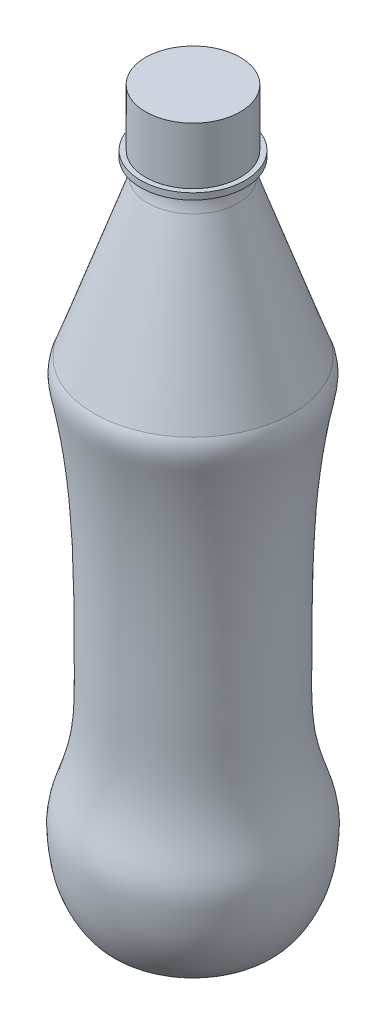
SolidWorks part; units mm, degrees
ref_plane "Front Plane" through (0, 0, 0) normal (0, 0, 1) x (1, 0, 0)
ref_plane "Top Plane" through (0, 0, 0) normal (0, 1, 0) x (1, 0, 0)
ref_plane "Right Plane" through (0, 0, 0) normal (1, 0, 0) x (0, 0, -1)
sketch "Sketch2" plane through (0, 0, 0) normal (0, 0, 1) x (1, 0, 0)
  line L0 (0, 168.9032) -> (0, -61.0968) construction
  line L1 (0, 168.9032) -> (15, 168.9032)
  line L2 (15, 168.9032) -> (15, 150.9032)
  line L3 (15, 150.9032) -> (16.6, 150.9032)
  line L4 (16.6, 150.9032) -> (16.6, 148.9032)
  line L5 (0, 148.9032) -> (13.5, 148.9032) construction
  line L6 (16.6, 148.9032) -> (13.5, 148.9032)
  line L7 (0, 88.9032) -> (32.5, 88.9032) construction
  line L8 (0, -36.0968) -> (32.75, -36.0968) construction
  line L9 (0, -31.0968) -> (32.7, -31.0968) construction
  line L10 (0, -21.0968) -> (30, -21.0968) construction
  line L11 (0, -11.0968) -> (27.6, -11.0968) construction
  line L12 (14.3221, 143.4974) -> (31.45, 94.2716)
  line L13 (0, 8.9032) -> (26.65, 8.9032) construction
  line L14 (0, 168.9032) -> (0, -55.3348)
  line L16 (0, 83.9032) -> (31.7, 83.9032) construction
  spline S0 degree 3 poles (13.5, 148.9032) (13.4345, 147.0626) (13.7086, 145.2606) (14.3221, 143.4974) knots 0 0 0 0 1 1 1 1
  spline S1 degree 3 poles (31.45, 94.2716) (33.2291, 90.845) (26.5516, 62.4338) (26.8239, 27.6424) (26.5349, -7.9803) (29.7799, -21.1671) (32.9574, -29.251) (32.6954, -40.3545) (31.0423, -50.9398) (22.168, -63.1456) (13.0307, -58.7237) (6.8276, -55.3682) (1.9563, -55.269) (0, -55.3348) knots 0 0 0 0 0.057803 0.472965 0.582838 0.63927 0.696109 0.723548 0.819703 0.882565 0.920544 0.968756 1 1 1 1
  dimension "D1" = 2
  dimension "D2" = 15
  dimension "D3" = 18
  dimension "D4" = 150
  dimension "D5" = 230
  dimension "D6" = 32.5
  dimension "D7" = 32.75
  dimension "D8" = 25
  dimension "D9" = 30
  dimension "D10" = 32.7
  dimension "D11" = 40
  dimension "D12" = 30
  dimension "D13" = 50
  dimension "D14" = 27.6
  dimension "D16" = 70
  dimension "D20" = 31.7
  dimension "D23" = 145
  dimension "D25" = 26.65
revolve "Revolve2" add sketch "Sketch2" angle 360 about L14
ref_plane "Plane1" through (0, -61, 0) normal (0, -1, 0) x (-1, 0, 0)
sketch "Sketch3" plane through (0, -61, 0) normal (0, -1, 0) x (-1, 0, 0)
  circle A0 centre (0, 0) radius 25.294
